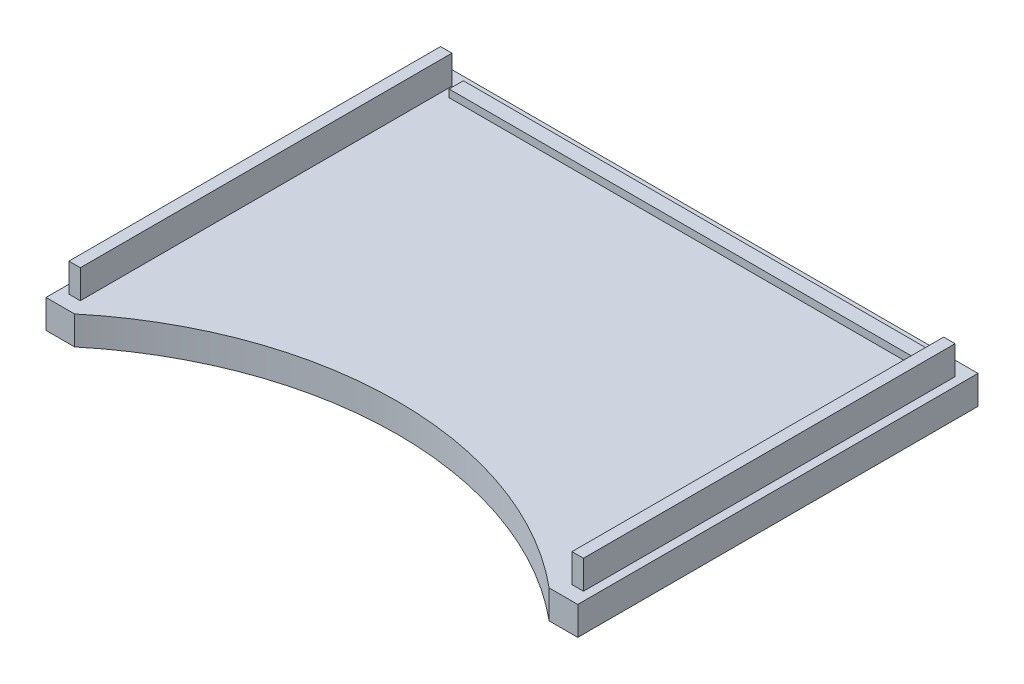
SolidWorks part; units mm, degrees
ref_plane "Front Plane" through (0, 0, 0) normal (0, 0, 1) x (1, 0, 0)
ref_plane "Top Plane" through (0, 0, 0) normal (0, 1, 0) x (1, 0, 0)
ref_plane "Right Plane" through (0, 0, 0) normal (1, 0, 0) x (0, 0, -1)
sketch "Sketch1" plane through (0, 0, 0) normal (0, 1, 0) x (1, 0, 0)
  line L1 (0, 0) -> (186, 0)
  line L2 (0, 0) -> (0, 140)
  line L3 (0, 140) -> (186, 140)
  line L4 (186, 0) -> (186, 140)
  dimension "D1" = 140
  dimension "D2" = 186
extrude "Boss-Extrude1" add sketch "Sketch1" along normal blind 10
sketch "Sketch4" plane through (0, 10, 0) normal (0, 1, 0) x (1, 0, 0)
  line L0 (186, 0) -> (186, 140) construction
  line L1 (186, 140) -> (0, 140) construction
  line L2 (10, 136) -> (176, 136)
  line L3 (10, 136) -> (10, 131)
  line L4 (10, 131) -> (176, 131)
  line L7 (176, 136) -> (176, 131)
  line L8 (0, 140) -> (0, 0) construction
  dimension "D1" = 5
  dimension "D2" = 4
  dimension "D3" = 10
  dimension "D4" = 10
sketch "Sketch5" plane through (0, 10, 0) normal (0, 1, 0) x (1, 0, 0)
  line L0 (10, 0) -> (10, 37.3827) construction
  line L1 (0, 0) -> (186, 0) construction
  line L2 (176, 0) -> (176, 15.4365) construction
  line L3 (0, 140) -> (0, 0) construction
  line L4 (186, 0) -> (186, 140) construction
  line L5 (93, 30) -> (0, 30) construction
  line L6 (176, 0) -> (10, 0)
  arc A0 (10, 0) -> (176, 0) centre (93, -99.8167) cw
  dimension "D1" = 10
  dimension "D2" = 10
  dimension "D3" = 30
extrude "Cut-Extrude5" cut sketch "Sketch5" against normal through all
extrude "Boss-Extrude3" add sketch "Sketch4" along normal blind 2.6416
sketch "Sketch6" plane through (0, 10, 0) normal (0, 1, 0) x (1, 0, 0)
  line L0 (186, 140) -> (0, 140) construction
  line L1 (179, 135) -> (183, 135)
  line L2 (179, 135) -> (179, 5)
  line L3 (179, 5) -> (183, 5)
  line L4 (183, 135) -> (183, 5)
  line L5 (176, 0) -> (186, 0) construction
  line L6 (186, 0) -> (186, 140) construction
  dimension "D1" = 5
  dimension "D2" = 5
  dimension "D3" = 3
  dimension "D4" = 4
extrude "Boss-Extrude4" add sketch "Sketch6" along normal blind 10
sketch "Sketch7" plane through (0, 10, 0) normal (0, 1, 0) x (1, 0, 0)
  line L0 (186, 140) -> (0, 140) construction
  line L1 (3, 135) -> (7, 135)
  line L2 (3, 135) -> (3, 5)
  line L3 (3, 5) -> (7, 5)
  line L4 (7, 135) -> (7, 5)
  line L5 (0, 0) -> (10, 0) construction
  line L6 (0, 140) -> (0, 0) construction
  line L7 (10, 136) -> (10, 131) construction
  dimension "D1" = 5
  dimension "D2" = 5
  dimension "D3" = 3
  dimension "D4" = 3
extrude "Boss-Extrude5" add sketch "Sketch7" along normal blind 10
